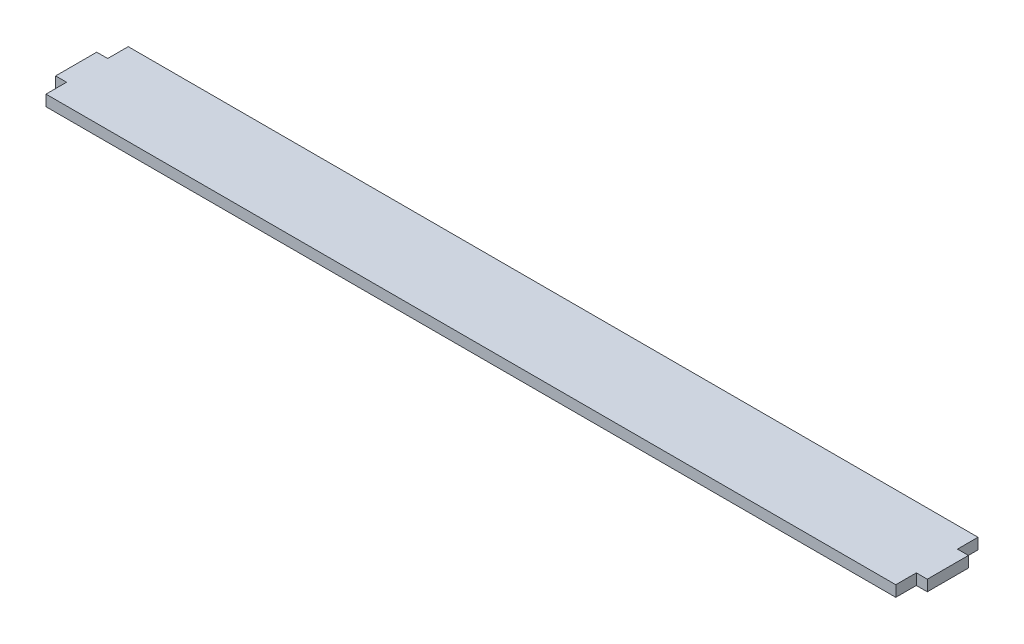
SolidWorks part; units mm, degrees
ref_plane "Piano frontale" through (0, 0, 0) normal (0, 0, 1) x (1, 0, 0)
ref_plane "Piano superiore" through (0, 0, 0) normal (0, 1, 0) x (1, 0, 0)
ref_plane "Piano destro" through (0, 0, 0) normal (1, 0, 0) x (0, 0, -1)
sketch "Schizzo1" plane through (0, 0, 0) normal (0, 1, 0) x (1, 0, 0)
  line L1 (-155, 15) -> (155, 15)
  line L2 (-155, 15) -> (-155, -15)
  line L3 (-155, -15) -> (155, -15)
  line L4 (155, 15) -> (155, -15)
  line L5 (-155, 15) -> (155, -15) construction
  line L6 (-155, -15) -> (155, 15) construction
  line L7 (-155, 7.5) -> (-159, 7.5)
  line L8 (-155, 7.5) -> (-155, -7.5)
  line L9 (-155, -7.5) -> (-159, -7.5)
  line L10 (-159, 7.5) -> (-159, -7.5)
  line L11 (155, 7.5) -> (159, 7.5)
  line L12 (155, 7.5) -> (155, -7.5)
  line L13 (155, -7.5) -> (159, -7.5)
  line L14 (159, 7.5) -> (159, -7.5)
  point P0 (0, 0)
  dimension "D1" = 30
  dimension "D2" = 310
  dimension "D3" = 4
  dimension "D4" = 15
  dimension "D5" = 7.5
  dimension "D6" = 15
  dimension "D7" = 7.5
  dimension "D8" = 4
extrude "Estrusione-Estrusione1" add sketch "Schizzo1" along normal blind 4 contours L14 L11 L4 L13 | L10 L9 L8 L7
